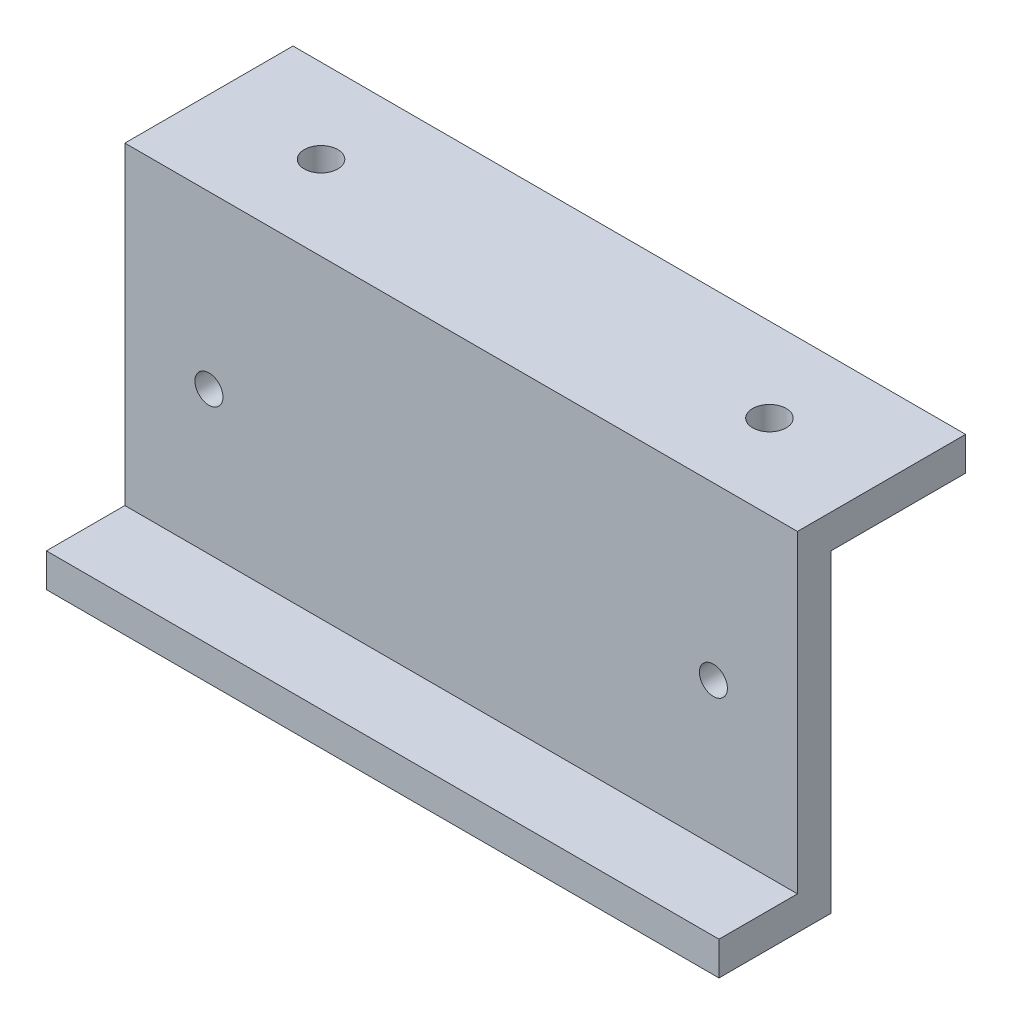
SolidWorks part; units mm, degrees
ref_plane "Front Plane" through (0, 0, 0) normal (0, 0, 1) x (1, 0, 0)
ref_plane "Top Plane" through (0, 0, 0) normal (0, 1, 0) x (1, 0, 0)
ref_plane "Right Plane" through (0, 0, 0) normal (1, 0, 0) x (0, 0, -1)
sketch "Sketch1" plane through (0, 0, 0) normal (0, 0, 1) x (1, 0, 0)
  line L0 (7.5, 12.75) -> (52.5, 12.75) construction
  line L1 (0, 0) -> (60, 0)
  line L2 (0, 0) -> (0, 25)
  line L3 (0, 25) -> (60, 25)
  line L4 (60, 0) -> (60, 25)
  line L5 (30, 12.75) -> (30, 20.75) construction
  circle A0 centre (7.5, 12.75) radius 1.25
  circle A1 centre (52.5, 12.75) radius 1.25
  point P11 (0, 0)
  point P12 (0, 0)
  dimension "D3" = 2.5
  dimension "D6" = 8
  dimension "D1" = 60
  dimension "D2" = 25
  dimension "D4" = 12.25
  dimension "D5" = 45
  dimension "D7" = 30
extrude "Boss-Extrude1" add sketch "Sketch1" along normal blind 3
sketch "Sketch2" plane through (0, 0, 0) normal (0, -1, 0) x (1, 0, 0)
  line L1 (0, 0) -> (60, 0)
  line L2 (0, 0) -> (0, 10)
  line L3 (0, 10) -> (60, 10)
  line L4 (60, 0) -> (60, 10)
  dimension "D1" = 60
  dimension "D2" = 10
extrude "Boss-Extrude2" add sketch "Sketch2" along normal blind 3
sketch "Sketch3" plane through (0, 25, 0) normal (0, 1, 0) x (1, 0, 0)
  line L1 (0, -3) -> (60, -3)
  line L2 (0, -3) -> (0, 12)
  line L3 (0, 12) -> (60, 12)
  line L4 (60, -3) -> (60, 12)
  dimension "D1" = 60
  dimension "D2" = 15
extrude "Boss-Extrude3" add sketch "Sketch3" along normal blind 3
sketch "Sketch4" plane through (0, 28, 0) normal (0, 1, 0) x (1, 0, 0)
  line L0 (0, 12) -> (0, -3) construction
  line L1 (60, 12) -> (0, 12) construction
  circle A0 centre (10, 4.5) radius 1.5
  circle A1 centre (50, 4.5) radius 1.5
  dimension "D4" = 3
  dimension "D5" = 3
  dimension "D1" = 40
  dimension "D2" = 10
  dimension "D3" = 7.5
extrude "Cut-Extrude1" cut sketch "Sketch4" against normal blind 3
